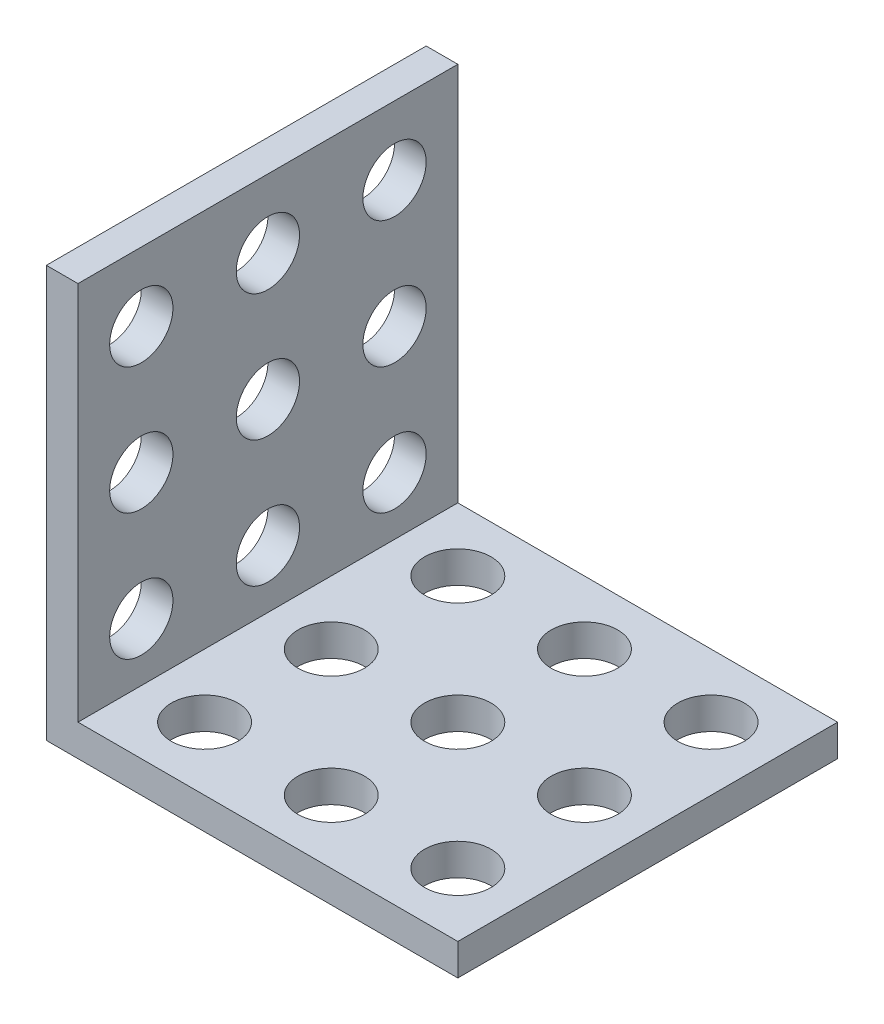
SolidWorks part; units mm, degrees
ref_plane "前视基准面" through (0, 0, 0) normal (0, 0, 1) x (1, 0, 0)
ref_plane "上视基准面" through (0, 0, 0) normal (0, 1, 0) x (1, 0, 0)
ref_plane "右视基准面" through (0, 0, 0) normal (1, 0, 0) x (0, 0, -1)
other "Configuration Table"
sketch "Sketch1" plane through (0, 0, 0) normal (0, 1, 0) x (1, 0, 0)
  line L1 (0, -12) -> (24, -12)
  line L2 (0, -12) -> (0, 12)
  line L3 (0, 12) -> (24, 12)
  line L4 (24, -12) -> (24, 12)
  line L5 (0, -12) -> (24, 12) construction
  line L6 (0, 12) -> (24, -12) construction
  circle A0 centre (4, 8) radius 2.1
  circle A1 centre (12, 8) radius 2.1
  circle A2 centre (20, 8) radius 2.1
  circle A3 centre (12, 0) radius 2.1
  circle A4 centre (20, 0) radius 2.1
  circle A5 centre (12, -8) radius 2.1
  circle A6 centre (20, -8) radius 2.1
  circle A7 centre (4, 0) radius 2.1
  circle A8 centre (4, -8) radius 2.1
  point P4 (12, 0)
  dimension "D3" = 4.2
  dimension "D1" = 24
  dimension "D2" = 24
  dimension "D4" = 4
  dimension "D5" = 3
  dimension "D6" = 3
extrude "Boss-Extrude1" add sketch "Sketch1" along normal blind 2
sketch "Sketch2" plane through (0, 0, 0) normal (-1, 0, 0) x (0, 0, 1)
  line L0 (12, 2) -> (12, 0) construction
  line L1 (-12, 0) -> (12, 0)
  line L2 (-12, 0) -> (-12, 26)
  line L3 (-12, 26) -> (12, 26)
  line L4 (12, 0) -> (12, 26)
  line L5 (-12, 0) -> (12, 26) construction
  line L6 (-12, 26) -> (12, 0) construction
  line L7 (-12, 2) -> (12, 2) construction
  circle A0 centre (-8, 21.6667) radius 2
  circle A1 centre (0, 21.6667) radius 2
  circle A2 centre (8, 21.6667) radius 2
  circle A3 centre (0, 13.6667) radius 2
  circle A4 centre (8, 13.6667) radius 2
  circle A5 centre (0, 5.6667) radius 2
  circle A6 centre (8, 5.6667) radius 2
  circle A7 centre (-8, 13.6667) radius 2
  circle A8 centre (-8, 5.6667) radius 2
  point P4 (0, 13)
  dimension "D2" = 4
  dimension "D1" = 24
  dimension "D3" = 4
  dimension "D4" = 3
  dimension "D5" = 3
extrude "Boss-Extrude2" add sketch "Sketch2" along normal blind 2
